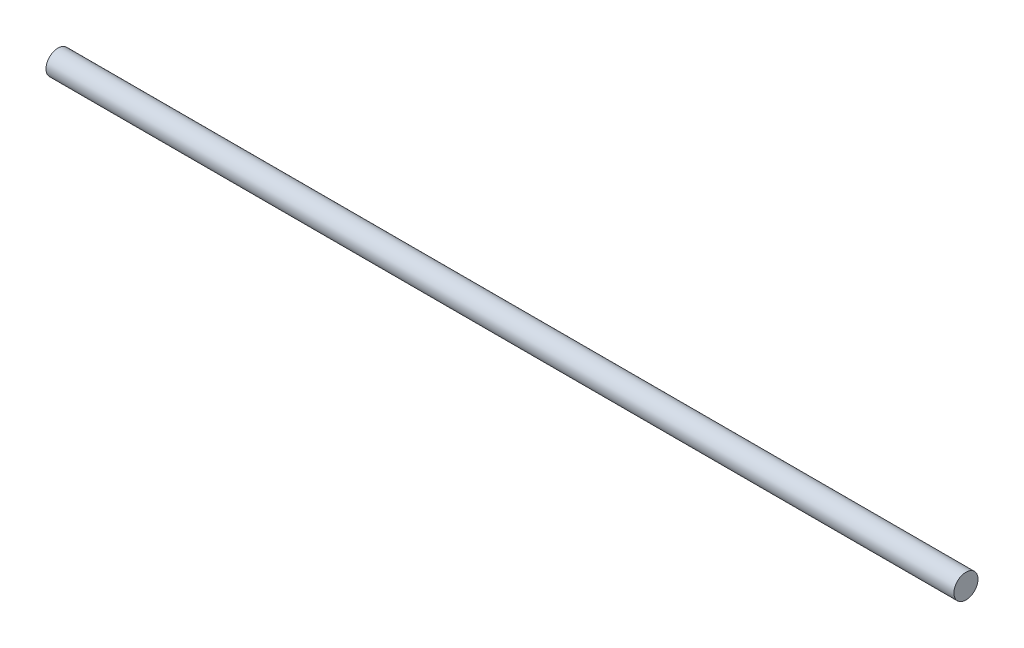
SolidWorks part; units mm, degrees
ref_plane "Front Plane" through (0, 0, 0) normal (0, 0, 1) x (1, 0, 0)
ref_plane "Top Plane" through (0, 0, 0) normal (0, 1, 0) x (1, 0, 0)
ref_plane "Right Plane" through (0, 0, 0) normal (1, 0, 0) x (0, 0, -1)
sketch "Sketch1" plane through (0, 0, 0) normal (1, 0, 0) x (0, 0, -1)
  circle A0 centre (0, 0) radius 3.985
  dimension "D1" = 7.97
extrude "Boss-Extrude1" add sketch "Sketch1" along normal mid plane 300
